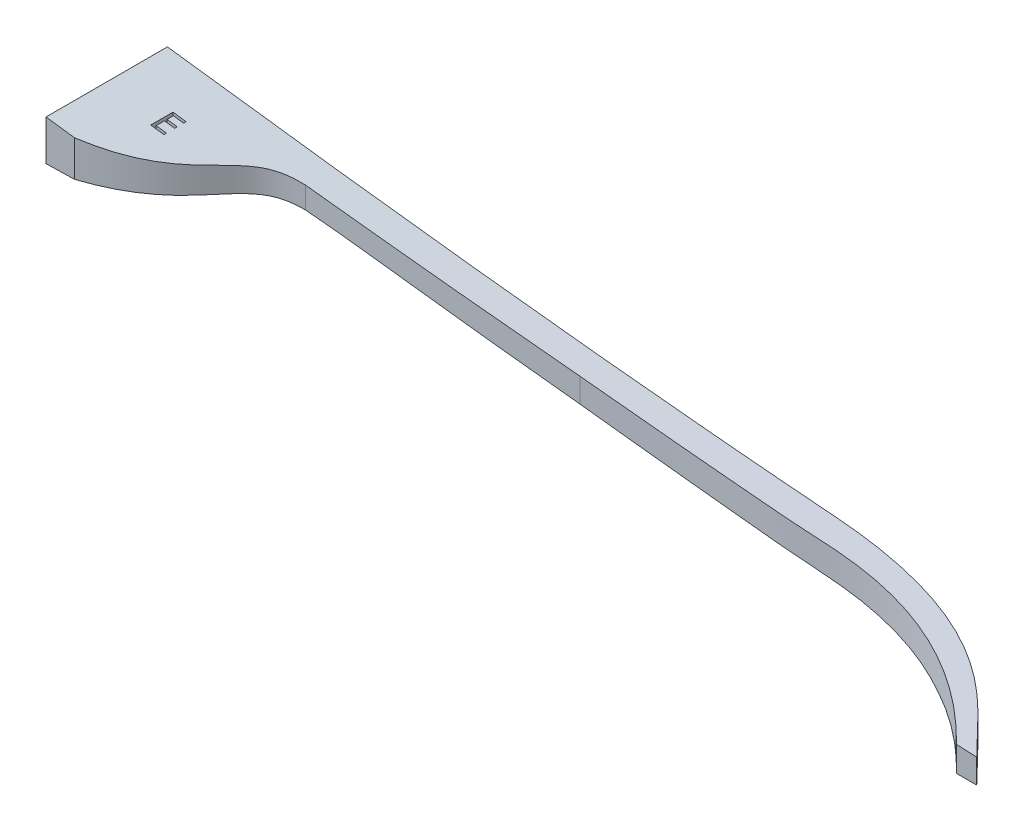
SolidWorks part; units mm, degrees
ref_plane "Front Plane" through (0, 0, 0) normal (0, 0, 1) x (1, 0, 0)
ref_plane "Top Plane" through (0, 0, 0) normal (0, 1, 0) x (1, 0, 0)
ref_plane "Right Plane" through (0, 0, 0) normal (1, 0, 0) x (0, 0, -1)
sketch "Sketch1" plane through (0, 0, 0) normal (0, 1, 0) x (1, 0, 0)
  line L1 (0, 0) -> (146.05, 0)
  line L2 (0, 0) -> (0, 19.05)
  line L3 (0, 19.05) -> (146.05, 19.05)
  line L4 (146.05, 0) -> (146.05, 19.05)
  dimension "D1" = 146.05
  dimension "D2" = 19.05
extrude "Boss-Extrude1" add sketch "Sketch1" along normal blind 17.78
sketch "Sketch3" plane through (0, 0, -19.05) normal (0, 0, -1) x (-1, 0, 0)
  line L0 (0, 17.78) -> (0, 0) construction
  line L1 (-146.05, 17.78) -> (-146.05, 0) construction
  spline S0 degree 3 poles (0, 11.43) (-27.213, 12.1419) (-25.4692, 9.8311) (-140.0169, -1.8119) (-146.05, 0) knots 0 0 0 0 0.551608 1 1 1 1
  spline S1 degree 3 poles (0, 17.78) (-48.4811, 11.3765) (-97.1678, 5.9127) (-146.05, 3.81) knots 0 0 0 0 1 1 1 1
  point P6 (-65.6621, 5.4839)
  point P11 (-64.8278, 9.0843)
  point P13 (0, 0)
  point P14 (0, 0)
  point P18 (-60.6733, 6.7531)
  line M1 (-146.05, 0) -> (0, 0)
  line M2 (0, 0) -> (0, 17.78)
  line M3 (0, 17.78) -> (-146.05, 17.78)
  line M4 (-146.05, 17.78) -> (-146.05, 0)
  dimension "D1" = 6.35
  dimension "D2" = 3.81
  dimension "D3" = 4.445
  dimension "D4" = 3.6908
sketch "Sketch6" plane through (0, 17.78, 0) normal (0, 1, 0) x (1, 0, 0)
  text T0 "<b>E</b>"
  point P1 (7.7865, 8.1993)
extrude "Cut-Extrude5" cut sketch "Sketch6" against normal blind 1.905
sketch "Sketch4" plane through (0, 17.78, 0) normal (0, 1, 0) x (1, 0, 0)
  line L0 (146.05, 19.05) -> (0, 19.05) construction
  line L3 (4.4767, 0) -> (142.875, 0)
  line L4 (146.05, 0) -> (146.05, 19.05)
  line L5 (146.05, 19.05) -> (104.3032, 19.05)
  line L6 (0, 0) -> (146.05, 0) construction
  line L7 (146.05, 0) -> (146.05, 19.05) construction
  spline S0 degree 3 poles (4.4767, 0) (17.7258, 4.0431) (17.0053, 14.2049) (37.6932, 14.9861) (95.0665, 14.824) (108.0685, 14.714) (127.2268, 16.0497) (142.875, 0) knots 0 0 0 0 0.256127 0.322877 0.629203 0.700745 1 1 1 1
  spline S1 degree 3 poles (104.3032, 19.05) (131.3235, 19.1838) (139.2243, 6.6595) (146.05, 0) knots 0 0 0 0 1 1 1 1
  spline S2 degree 1 poles (26.2195, 14.4658) (68.9239, 14.8611) knots 0 0 1 1
  line M2 (146.05, 19.05) -> (0, 19.05)
  line M4 (0, 0) -> (146.05, 0)
  dimension "D1" = 3.175
extrude "Cut-Extrude2" cut sketch "Sketch4" against normal blind 19.05 contours S2 S0 M4 | S1 L4 M2
extrude "Cut-Extrude3" cut sketch "Sketch3" against normal through all contours S0 M2 M1 | S1 M3 M4
sketch "Sketch5" plane through (0, 0, 0) normal (-1, 0, 0) x (0, 0, 1)
  line L0 (0, 11.43) -> (-19.05, 11.43) construction
  line L1 (-5.715, 11.43) -> (-12.7, 11.43)
  line L2 (-5.715, 11.43) -> (-5.715, 15.24)
  line L3 (-5.715, 15.24) -> (-12.7, 15.24)
  line L4 (-12.7, 11.43) -> (-12.7, 15.24)
  line L5 (-19.05, 17.78) -> (-19.05, 11.43) construction
  dimension "D1" = 3.81
  dimension "D2" = 6.985
  dimension "D3" = 6.35
extrude "Cut-Extrude4" cut sketch "Sketch5" against normal blind 6.35
